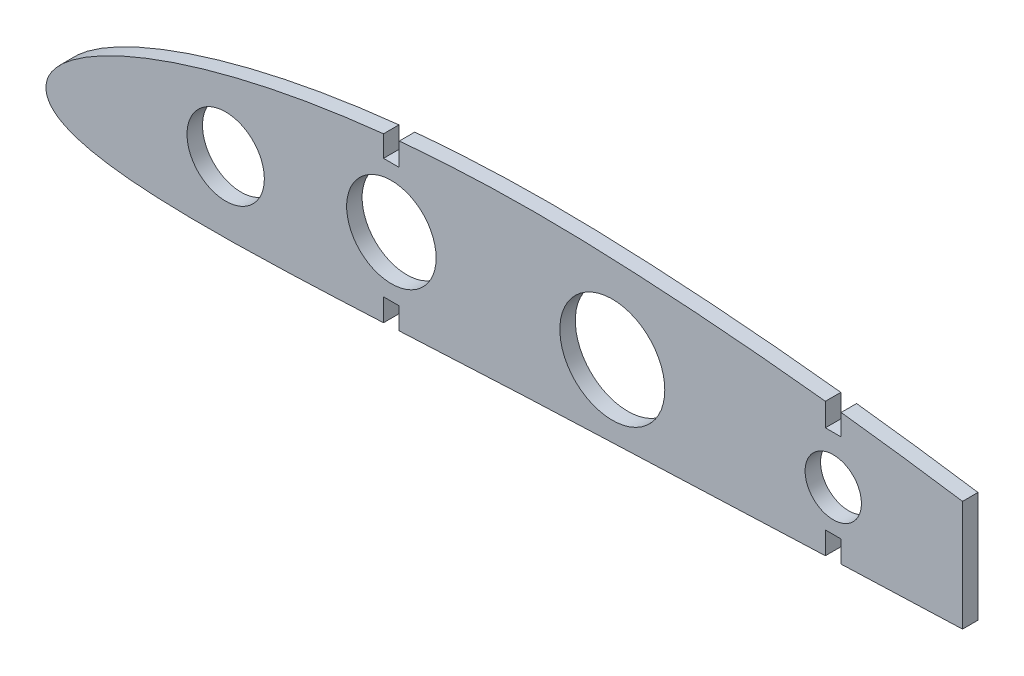
SolidWorks part; units mm, degrees
material "Фанера"
ref_plane "Front Plane" through (0, 0, 0) normal (0, 0, 1) x (1, 0, 0)
ref_plane "Top Plane" through (0, 0, 0) normal (0, 1, 0) x (1, 0, 0)
ref_plane "Right Plane" through (0, 0, 0) normal (1, 0, 0) x (0, 0, -1)
curve "Кривая5"
  spline degree 3 poles (0.048, 0.6214, 0) (0.0227, 0.3735, 0) (-0.0278, -0.1225, 0) (0.078, -0.8844, 0) (0.3497, -1.6388, 0) (0.8143, -2.3651, 0) (1.4635, -3.0393, 0) (2.291, -3.661, 0) (3.3059, -4.2358, 0) (4.5353, -4.7737, 0) (6.0297, -5.2822, 0) (7.869, -5.7653, 0) (10.1688, -6.2217, 0) (13.0754, -6.6396, 0) (16.7281, -6.993, 0) (21.19, -7.2473, 0) (26.4, -7.3766, 0) (32.1974, -7.3763, 0) (38.3978, -7.2614, 0) (44.8576, -7.0566, 0) (51.4865, -6.7865, 0) (58.231, -6.4723, 0) (65.0521, -6.1329, 0) (71.9108, -5.784, 0) (78.7714, -5.4397, 0) (85.6105, -5.111, 0) (92.4321, -4.805, 0) (99.255, -4.532, 0) (106.0974, -4.2783, 0) (112.9692, -4.0031, 0) (119.8644, -3.7232, 0) (126.7739, -3.4401, 0) (133.6816, -3.1587, 0) (140.5819, -2.8824, 0) (147.472, -2.6139, 0) (154.3526, -2.3556, 0) (161.225, -2.1094, 0) (168.0909, -1.8766, 0) (174.9516, -1.6586, 0) (181.8086, -1.4564, 0) (188.6632, -1.2704, 0) (195.5166, -1.1011, 0) (202.3695, -0.9486, 0) (209.2212, -0.8129, 0) (216.0668, -0.6936, 0) (222.8864, -0.5903, 0) (229.6176, -0.5029, 0) (236.0874, -0.4315, 0) (241.9808, -0.3765, 0) (246.559, -0.3395, 0) (249.1205, -0.3213, 0) (250, -0.315, 0) knots 0 0 0 0 0.002941 0.005884 0.009016 0.012365 0.016008 0.020037 0.024574 0.029784 0.035897 0.04324 0.052276 0.063635 0.077983 0.095698 0.11652 0.139661 0.164312 0.189919 0.216157 0.242838 0.269834 0.296993 0.324123 0.351139 0.378036 0.404946 0.431961 0.459078 0.486347 0.513641 0.540929 0.568176 0.59538 0.622543 0.649673 0.676775 0.703855 0.730919 0.757971 0.785018 0.812062 0.839103 0.866132 0.893099 0.919831 0.94581 0.969681 0.98959 1 1 1 1
curve "Кривая6"
  spline degree 3 poles (250, 0.315, 0) (249.1557, 0.545, 0) (246.7202, 1.2085, 0) (242.3913, 2.3583, 0) (236.8498, 3.7876, 0) (230.7799, 5.298, 0) (224.4559, 6.8129, 0) (218.0305, 8.2916, 0) (211.5624, 9.7197, 0) (205.0724, 11.0924, 0) (198.568, 12.4079, 0) (192.0524, 13.6653, 0) (185.5276, 14.8641, 0) (178.9953, 16.0034, 0) (172.4571, 17.0824, 0) (165.9143, 18.0998, 0) (159.3687, 19.0545, 0) (152.8218, 19.9449, 0) (146.2754, 20.7693, 0) (139.7314, 21.5257, 0) (133.1918, 22.212, 0) (126.6587, 22.8257, 0) (120.1368, 23.364, 0) (113.6286, 23.8247, 0) (107.1527, 24.2002, 0) (100.7411, 24.4984, 0) (94.4118, 24.6866, 0) (88.1559, 24.7401, 0) (81.949, 24.6588, 0) (75.7805, 24.441, 0) (69.6537, 24.0819, 0) (63.5754, 23.578, 0) (57.5552, 22.9249, 0) (51.6058, 22.1191, 0) (45.7444, 21.1566, 0) (39.9959, 20.0354, 0) (34.3979, 18.7563, 0) (29.0104, 17.3276, 0) (23.9258, 15.7719, 0) (19.2707, 14.1343, 0) (15.1791, 12.4833, 0) (11.7405, 10.8956, 0) (8.9594, 9.4296, 0) (6.7609, 8.1086, 0) (5.0337, 6.9246, 0) (3.6717, 5.8542, 0) (2.5921, 4.8713, 0) (1.7382, 3.9526, 0) (1.0699, 3.0809, 0) (0.5716, 2.2416, 0) (0.2158, 1.4308, 0) (0.1023, 0.8832, 0) (0.048, 0.6214, 0) knots 0 0 0 0 0.010162 0.029313 0.052012 0.076619 0.101948 0.127526 0.153184 0.178868 0.204558 0.230246 0.255926 0.281594 0.307246 0.332878 0.358485 0.384061 0.409603 0.435104 0.460559 0.485959 0.511303 0.536552 0.561723 0.586629 0.611085 0.635251 0.659272 0.683164 0.706922 0.730536 0.753983 0.777235 0.800246 0.822951 0.845237 0.866916 0.887662 0.906968 0.924203 0.938879 0.950932 0.960693 0.968647 0.975233 0.980795 0.985584 0.989782 0.993521 0.996902 1 1 1 1
sketch "Эскиз1" plane through (0, 0, 0) normal (0, 0, 1) x (1, 0, 0)
  line L0 (250.1305, 0) -> (250.1305, 54.8427) construction
  line L1 (0, 0) -> (0, 70.5199) construction
  line L2 (0, 0) -> (253.0634, 0) construction
  line L3 (62.5326, 62.6361) -> (62.5326, -41.5636) construction
  line L4 (142.5326, 67.9319) -> (142.5326, 25.1988) construction
  line L5 (175.0913, 63.8571) -> (175.0913, -32.3947) construction
  line L6 (32.5326, -14.3434) -> (32.5326, 29.5903) construction
  line L7 (142.5326, 21.1988) -> (142.5326, -57.0034) construction
  line L8 (61.1076, 19.4501) -> (63.9576, 19.4501)
  line L9 (61.1076, 19.4501) -> (61.1076, 23.3031)
  line L11 (63.9576, 19.4501) -> (63.9576, 23.5885)
  line L12 (61.1076, 19.4501) -> (62.5326, 23.4501) construction
  line L13 (62.5326, 23.4501) -> (63.9576, 19.4501) construction
  line L15 (61.1076, -6.3284) -> (61.1076, -2.2577)
  line L16 (61.1076, -2.2577) -> (63.9576, -2.2577)
  line L17 (63.9576, -6.1866) -> (63.9576, -2.2577)
  line L18 (62.5326, -6.2577) -> (63.9576, -2.2577) construction
  line L19 (61.1076, -2.2577) -> (62.5326, -6.2577) construction
  line L20 (141.1076, 17.1988) -> (143.9576, 17.1988)
  line L21 (141.1076, 17.1988) -> (141.1076, 21.3608)
  line L23 (143.9576, 17.1988) -> (143.9576, 21.0336)
  line L24 (141.1076, 17.1988) -> (142.5326, 21.1988) construction
  line L25 (142.5326, 21.1988) -> (143.9576, 17.1988) construction
  line L26 (165.9405, 18.0854) -> (165.9405, -1.9504)
  line L28 (141.1076, -2.8629) -> (141.1076, 1.1931)
  line L29 (141.1076, 1.1931) -> (143.9576, 1.1931)
  line L30 (143.9576, -2.7512) -> (143.9576, 1.1931)
  line L31 (142.5326, -2.8069) -> (143.9576, 1.1931) construction
  line L32 (141.1076, 1.1931) -> (142.5326, -2.8069) construction
  arc A0 (250, 0.315) -> (250, -0.315) centre (249.685, 0) cw
  circle A1 centre (62.5326, 8.5962) radius 8.1
  circle A2 centre (142.5326, 8.5962) radius 5.1
  circle A3 centre (32.5326, 5.4481) radius 7
  circle A5 centre (102.5326, 8.5962) radius 9.5
  arc A6 (175.0913, 16.6448) -> (175.0913, -1.657) centre (175.0913, 7.4939) ccw
  spline S2 degree 3 poles (0.048, 0.6214) (0.0227, 0.3735) (-0.0278, -0.1225) (0.078, -0.8844) (0.3497, -1.6388) (0.8143, -2.3651) (1.4635, -3.0393) (2.291, -3.661) (3.3059, -4.2358) (4.5353, -4.7737) (6.0297, -5.2822) (7.869, -5.7653) (10.1688, -6.2217) (13.0754, -6.6396) (16.7281, -6.993) (21.19, -7.2473) (26.4, -7.3766) (32.1974, -7.3763) (38.3978, -7.2614) (44.8576, -7.0566) (51.4865, -6.7865) (56.9206, -6.5334) (60.1398, -6.3761) (61.1076, -6.3284) knots 0 0 0 0 0.002941 0.005884 0.009016 0.012365 0.016008 0.020037 0.024574 0.029784 0.035897 0.04324 0.052276 0.063635 0.077983 0.095698 0.11652 0.139661 0.164312 0.189919 0.216157 0.242838 0.254307 0.254307 0.254307 0.254307
  spline S3 degree 3 poles (250, 0.315) (249.1557, 0.545) (246.7202, 1.2085) (242.3913, 2.3583) (236.8498, 3.7876) (230.7799, 5.298) (224.4559, 6.8129) (218.0305, 8.2916) (211.5624, 9.7197) (205.0724, 11.0924) (198.568, 12.4079) (192.0524, 13.6653) (185.5276, 14.8641) (178.9953, 16.0034) (172.4571, 17.0824) (165.9143, 18.0998) (159.3687, 19.0545) (152.8218, 19.9449) (147.6839, 20.5919) (144.7288, 20.9433) (143.9576, 21.0336) knots 0 0 0 0 0.010162 0.029313 0.052012 0.076619 0.101948 0.127526 0.153184 0.178868 0.204558 0.230246 0.255926 0.281594 0.307246 0.332878 0.358485 0.384061 0.409603 0.418619 0.418619 0.418619 0.418619
  spline S4 degree 3 poles (61.1076, 23.3031) (59.9179, 23.1768) (56.7397, 22.8145) (51.6058, 22.1191) (45.7444, 21.1566) (39.9959, 20.0354) (34.3979, 18.7563) (29.0104, 17.3276) (23.9258, 15.7719) (19.2707, 14.1343) (15.1791, 12.4833) (11.7405, 10.8956) (8.9594, 9.4296) (6.7609, 8.1086) (5.0337, 6.9246) (3.6717, 5.8542) (2.5921, 4.8713) (1.7382, 3.9526) (1.0699, 3.0809) (0.5716, 2.2416) (0.2158, 1.4308) (0.1023, 0.8832) (0.048, 0.6214) knots 0.740091 0.740091 0.740091 0.740091 0.753983 0.777235 0.800246 0.822951 0.845237 0.866916 0.887662 0.906968 0.924203 0.938879 0.950932 0.960693 0.968647 0.975233 0.980795 0.985584 0.989782 0.993521 0.996902 1 1 1 1
  spline S5 degree 3 poles (63.9576, -6.1866) (64.3178, -6.1685) (66.9697, -6.0353) (71.9108, -5.784) (78.7714, -5.4397) (85.6105, -5.111) (92.4321, -4.805) (99.255, -4.532) (106.0974, -4.2783) (112.9692, -4.0031) (119.8644, -3.7232) (126.7739, -3.4401) (133.8556, -3.1516) (138.6334, -2.9604) (141.1076, -2.8629) knots 0.265565 0.265565 0.265565 0.265565 0.269834 0.296993 0.324123 0.351139 0.378036 0.404946 0.431961 0.459078 0.486347 0.513641 0.540929 0.570237 0.570237 0.570237 0.570237
  spline S6 degree 3 poles (143.9576, -2.7512) (145.1302, -2.7056) (148.5961, -2.5717) (154.3526, -2.3556) (161.225, -2.1094) (168.0909, -1.8766) (174.9516, -1.6586) (181.8086, -1.4564) (188.6632, -1.2704) (195.5166, -1.1011) (202.3695, -0.9486) (211.4992, -0.7677) (220.6031, -0.6199) (229.6176, -0.5029) (236.0874, -0.4315) (241.9808, -0.3765) (246.559, -0.3395) (249.1205, -0.3213) (250, -0.315) knots 0.58149 0.58149 0.58149 0.58149 0.59538 0.622543 0.649673 0.676775 0.703855 0.730919 0.757971 0.785018 0.812062 0.839103 0.893099 0.919831 0.94581 0.969681 0.98959 1 1 1 1
  spline S7 degree 3 poles (141.1076, 21.3608) (140.6472, 21.4126) (138.0081, 21.7065) (133.1918, 22.212) (126.6587, 22.8257) (120.1368, 23.364) (113.6286, 23.8247) (107.1527, 24.2002) (100.7411, 24.4984) (94.4118, 24.6866) (88.1559, 24.7401) (81.949, 24.6588) (75.7805, 24.441) (69.7854, 24.0896) (65.8508, 23.7665) (63.9576, 23.5885) knots 0.429724 0.429724 0.429724 0.429724 0.435104 0.460559 0.485959 0.511303 0.536552 0.561723 0.586629 0.611085 0.635251 0.659272 0.683164 0.706922 0.729004 0.729004 0.729004 0.729004
  point P22 (62.5326, 23.4501)
  point P23 (62.5326, -6.2577)
  point P26 (32.5326, 18.2506)
  point P27 (32.5326, -7.3543)
  point P30 (62.5326, 23.4501)
  point P31 (62.5326, -6.2577)
  point P40 (142.5326, 21.1988)
  point P43 (142.5326, -2.8069)
  point P53 (175.0913, 16.6448)
  point P56 (175.0913, -1.657)
  point P62 (0, 0)
  point P63 (0, 0)
  point P64 (0, 0)
  point P65 (0, 0)
  dimension "D3" = 16.2
  dimension "D8" = 14
  dimension "D10" = 10.2
  dimension "D9" = 19
  dimension "D27" = 9.1509
  dimension "D1" = 250.1305
  dimension "D2" = 62.5326
  dimension "D4" = 80
  dimension "D5" = 75.0391
  dimension "D6" = 29.7079
  dimension "D7" = 14.8539
  dimension "D11" = 40
  dimension "D12" = 30
  dimension "D13" = 25.6049
  dimension "D14" = 12.8025
  dimension "D15" = 2.85
  dimension "D16" = 4
  dimension "D17" = 1.425
  dimension "D18" = 2.85
  dimension "D19" = 4
  dimension "D20" = 1.425
  dimension "D21" = 2.85
  dimension "D22" = 4
  dimension "D23" = 1.425
  dimension "D24" = 2.85
  dimension "D25" = 4
  dimension "D26" = 1.425
extrude "Бобышка-Вытянуть1" add sketch "Эскиз1" along normal mid plane 2.8 contours L21 S7 L11 L8 L9 S4 S2 L15 L16 L17 S5 L28 L29 L30 S6 L26 S3 L23 L20 A1 A2 A3 A5
equation "\"D2@Эскиз1\"=\"D1@Эскиз1\"/4"
equation "\"D7@Эскиз1\"=\"D6@Эскиз1\"/2"
equation "\"D5@Эскиз1\"=\"D1@Эскиз1\"*0.3"
equation "\"D14@Эскиз1\"=\"D13@Эскиз1\"/2"
equation "\"t\"= 2.85"
equation "\"D17@Эскиз1\"=\"D15@Эскиз1\"/2"
equation "\"D18@Эскиз1\"=\"t\""
equation "\"D20@Эскиз1\"=\"D18@Эскиз1\"/2"
equation "\"D21@Эскиз1\"=\"t\""
equation "\"D23@Эскиз1\"=\"D21@Эскиз1\"/2"
equation "\"D24@Эскиз1\"=\"t\""
equation "\"D26@Эскиз1\"=\"D24@Эскиз1\"/2"
